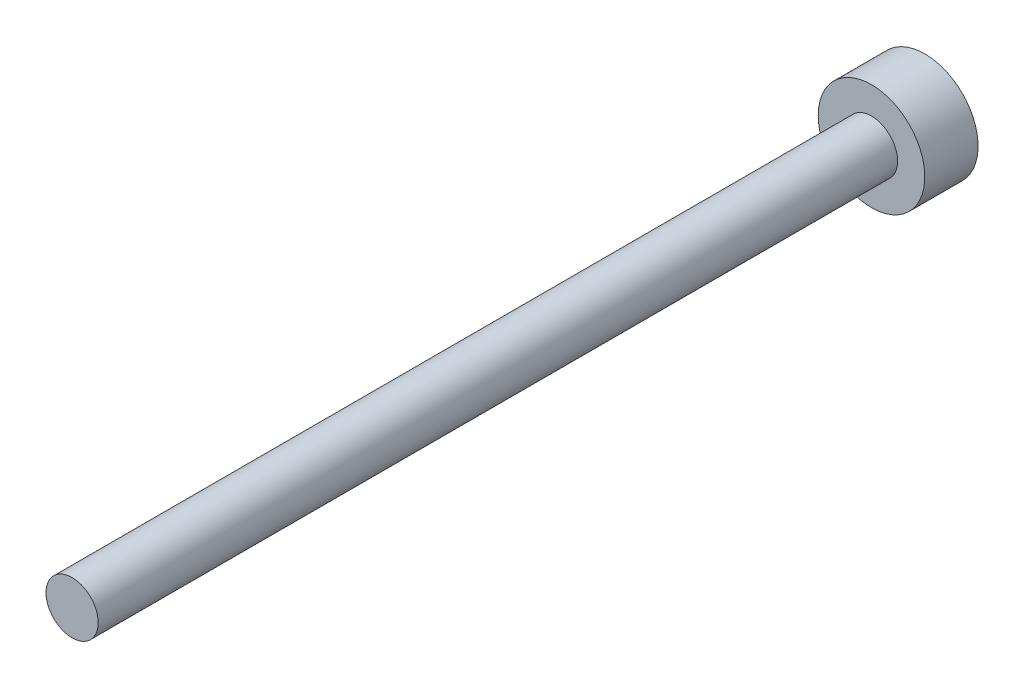
SolidWorks part; units mm, degrees
ref_plane "前视基准面" through (0, 0, 0) normal (0, 0, 1) x (1, 0, 0)
ref_plane "上视基准面" through (0, 0, 0) normal (0, 1, 0) x (1, 0, 0)
ref_plane "右视基准面" through (0, 0, 0) normal (1, 0, 0) x (0, 0, -1)
sketch "草图1" plane through (0, 0, 0) normal (0, 0, 1) x (1, 0, 0)
  circle A0 centre (0, 0) radius 2.45
  dimension "D1" = 4.9
extrude "凸台-拉伸1" add sketch "草图1" along normal blind 80
sketch "草图2" plane through (0, 0, 0) normal (0, 0, -1) x (-1, 0, 0)
  circle A0 centre (0, 0) radius 5
  dimension "D1" = 10
extrude "凸台-拉伸2" add sketch "草图2" against normal blind 5
